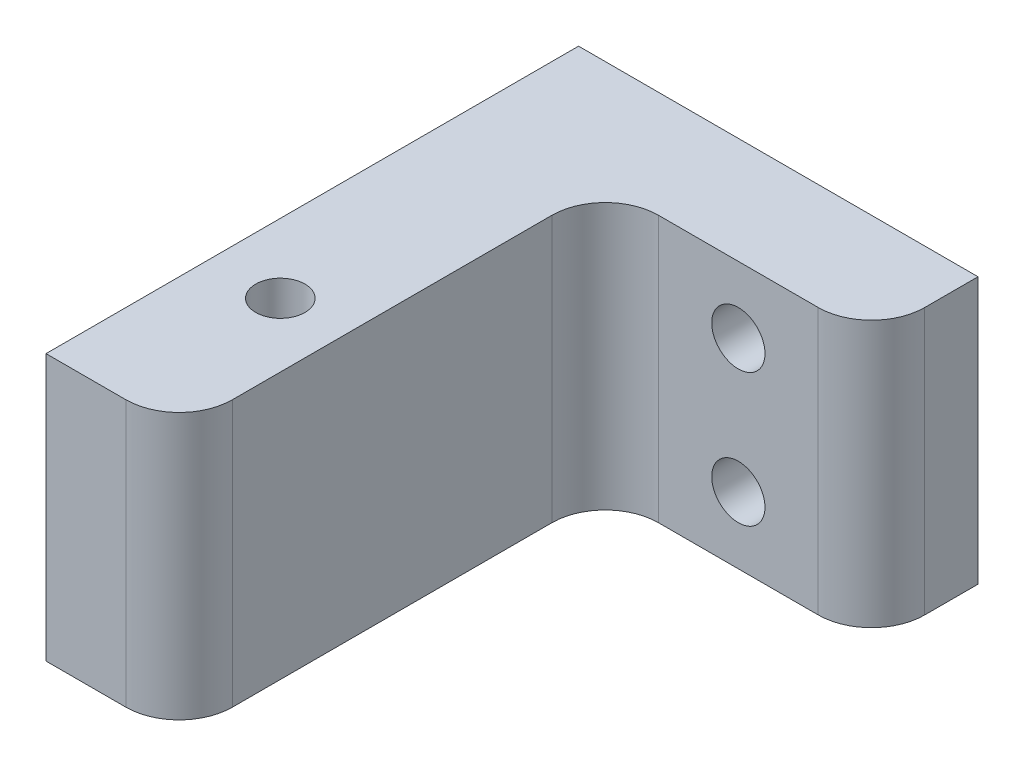
SolidWorks part; units mm, degrees
ref_plane "Front Plane" through (0, 0, 0) normal (0, 0, 1) x (1, 0, 0)
ref_plane "Top Plane" through (0, 0, 0) normal (0, 1, 0) x (1, 0, 0)
ref_plane "Right Plane" through (0, 0, 0) normal (1, 0, 0) x (0, 0, -1)
other "Configuration Table"
sketch "Sketch2" plane through (-29.3555, 0, 0) normal (1, 0, 0) x (0, 0, -1)
  line L2 (0, -16) -> (0, -6)
  line L13 (0, -16) -> (20, -16)
  line L14 (0, -6) -> (20, -6)
  line L15 (20, -6) -> (20, -16)
  line L18 (12.4, 0) -> (0, 0)
  line L19 (0, 0) -> (0, -16)
  line L20 (0, -16) -> (12.4, -16)
  line L21 (12.4, -16) -> (12.4, 0)
  line L23 (0, -6) -> (0, -16)
  line L24 (0, -16) -> (12.4, -16)
  line M7 (0, 0) -> (0, -16)
  line M8 (0, -16) -> (12.4, -16)
  line M9 (12.4, -16) -> (12.4, 0)
  dimension "D2" = 10
  dimension "D3" = 20
extrude "Boss-Extrude1" add sketch "Sketch2" along normal up to surface (5 mm away) contours L14 M7 M8 M9 | L15 L14 L13 M9
sketch "Sketch3" plane through (0, -16, 0) normal (0, -1, 0) x (-1, 0, 0)
  circle A0 centre (26.7555, 6.2) radius 1
  arc A1 (25.8187, 5.85) -> (25.8187, 6.55) centre (26.7555, 6.2) ccw construction
  circle A2 centre (26.7555, 6.2) radius 0.925
  dimension "D1" = 0.075
extrude "Cut-Extrude1" cut sketch "Sketch3" against normal up to surface (10 mm away) contours A2 up to face at (-26.8555, -6, -10)
sketch "Sketch4" plane through (-24.3555, 0, 0) normal (1, 0, 0) x (0, 0, -1)
  line L0 (20, -16) -> (0, -16) construction
  line L1 (16, -16) -> (20, -16)
  line L2 (16, -16) -> (16, -6)
  line L3 (16, -6) -> (20, -6)
  line L4 (20, -16) -> (20, -6)
  dimension "D1" = 4
extrude "Boss-Extrude2" add sketch "Sketch4" along normal blind 10
fillet "Fillet1" radius 2 3 edges at (-14.3555, -11, -16) (-24.3555, -11, -16) (-24.3555, -11, 0)
sketch "Sketch5" plane through (0, 0, -16) normal (0, 0, 1) x (1, 0, 0)
  line L0 (-19.3555, -6) -> (-19.3555, -16) construction
  line L1 (-22.3555, -11) -> (-16.3555, -11) construction
  line L4 (-22.3555, -16) -> (-16.3555, -16)
  line L5 (-16.3555, -16) -> (-16.3555, -6)
  line L6 (-16.3555, -6) -> (-22.3555, -6)
  line L7 (-22.3555, -6) -> (-22.3555, -16)
  line L8 (-22.3555, -16) -> (-16.3555, -16)
  line L9 (-16.3555, -16) -> (-16.3555, -6)
  line L10 (-16.3555, -6) -> (-22.3555, -6)
  line L11 (-22.3555, -6) -> (-22.3555, -16)
  circle A0 centre (-19.3555, -8.5) radius 1
  circle A1 centre (-19.3555, -13.5) radius 1
  dimension "D2" = 2
  dimension "D3" = 2.5
extrude "Cut-Extrude2" cut sketch "Sketch5" against normal up to surface (4 mm away) contours A0 | A1 up to face at (-21.8555, -11, -20)
equation "\"SW\"= 10'Width of Support"
equation "\"D2@Sketch2\"=\"SW\""
equation "\"C\"= 0.15mm'Clearance Gap"
equation "\"D1@Sketch3\"=\"C\"/2"
equation "\"SH\"= 20'Height of Support"
equation "\"D3@Sketch2\"=\"SH\""
equation "\"SL\"= 10'Length of Support"
equation "\"D1@Boss-Extrude2\"=\"SL\""
equation "\"F\"= 2mm'Fillet Radius"
equation "\"D1@Fillet1\"=\"F\""
equation "\"D3@Sketch5\"=\"SW\"/4"
